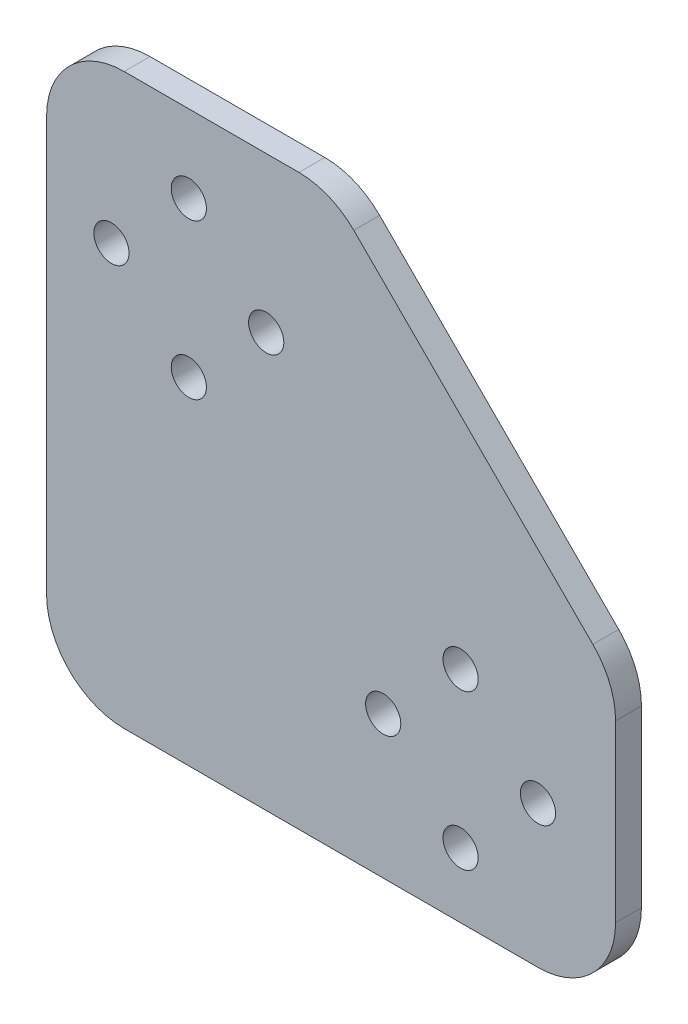
SolidWorks part; units mm, degrees
ref_plane "Front Plane" through (0, 0, 0) normal (0, 0, 1) x (1, 0, 0)
ref_plane "Top Plane" through (0, 0, 0) normal (0, 1, 0) x (1, 0, 0)
ref_plane "Right Plane" through (0, 0, 0) normal (1, 0, 0) x (0, 0, -1)
sketch "Sketch1" plane through (0, 0, 0) normal (0, 0, 1) x (1, 0, 0)
  line L0 (0, 0) -> (79.9193, 79.9193) construction
  line L1 (0, 0) -> (69.85, 0)
  line L2 (0, 0) -> (0, 69.85)
  line L3 (69.85, 0) -> (69.85, 34.925)
  line L4 (0, 69.85) -> (34.925, 69.85)
  line L5 (69.85, 34.925) -> (34.925, 69.85)
  line L6 (50.825, 26.9625) -> (50.825, 7.9625) construction
  line L7 (41.325, 17.4625) -> (60.325, 17.4625) construction
  circle A0 centre (50.825, 26.9625) radius 2.159
  circle A1 centre (26.9625, 50.825) radius 2.159
  circle A2 centre (50.825, 7.9625) radius 2.159
  circle A3 centre (7.9625, 50.825) radius 2.159
  circle A4 centre (41.325, 17.4625) radius 2.159
  circle A5 centre (17.4625, 41.325) radius 2.159
  circle A6 centre (60.325, 17.4625) radius 2.159
  circle A7 centre (17.4625, 60.325) radius 2.159
  point P8 (52.3875, 52.3875)
  point P12 (50.825, 17.4625)
  point P13 (50.825, 17.4625)
  point P14 (69.85, 17.4625)
  dimension "D6" = 4.318
  dimension "D1" = 69.85
  dimension "D2" = 45
  dimension "D3" = 34.925
  dimension "D4" = 19
  dimension "D5" = 60.325
extrude "Boss-Extrude1" add sketch "Sketch1" along normal mid plane 3.175
fillet "Fillet1" radius 9.525 5 edges at (34.925, 69.85, 0) (69.85, 34.925, 0) (0, 69.85, 0) (69.85, 0, 0) (0, 0, 0)
equation "\"od square tube\"= 1.375in"
equation "\"D3@Sketch1\"=\"od square tube\""
equation "\"D5@Sketch1\"=\"od square tube\"+1"
